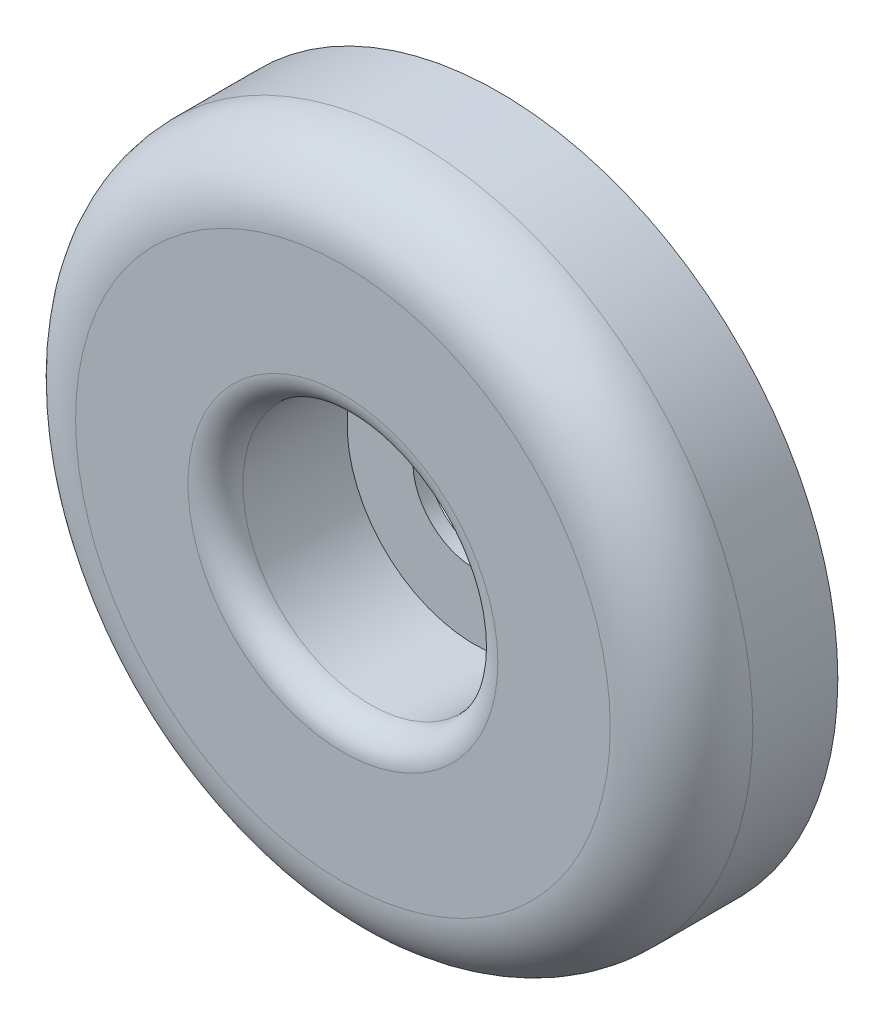
SolidWorks part; units mm, degrees
ref_plane "Plan de face" through (0, 0, 0) normal (0, 0, 1) x (1, 0, 0)
ref_plane "Plan de dessus" through (0, 0, 0) normal (0, 1, 0) x (1, 0, 0)
ref_plane "Plan de droite" through (0, 0, 0) normal (1, 0, 0) x (0, 0, -1)
sketch "Esquisse1" plane through (0, 0, 0) normal (1, 0, 0) x (0, 0, -1)
  line L0 (0, 0) -> (0, 2.25) construction
  line L1 (24.9343, 2.25) -> (-13.052, 2.25) construction
  line L2 (0, 2.25) -> (0.5, 2.25)
  line L3 (0.5, 2.25) -> (0.5, 4.65)
  line L6 (0.9, 12.35) -> (-2.1, 12.35)
  line L7 (0, 2.25) -> (0, 4.65)
  line L11 (-2.1, 12.35) -> (-2.2, 12.35)
  line L13 (-13.052, 0) -> (16.3888, 0) construction
  line L14 (-4.8, 9.75) -> (-4.8, 5.65)
  line L15 (-3.8, 4.65) -> (0, 4.65)
  line L16 (0.9, 12.35) -> (0.9, 4.65)
  line L17 (0.9, 4.65) -> (0.5, 4.65)
  arc A0 (-2.2, 12.35) -> (-4.8, 9.75) centre (-2.2, 9.75) ccw
  arc A1 (-4.8, 5.65) -> (-3.8, 4.65) centre (-3.8, 5.65) ccw
  dimension "D8" = 2.6
  dimension "D9" = 1
  dimension "D1" = 10.1
  dimension "D2" = 2.25
  dimension "D3" = 0.4
  dimension "D4" = 7.7
  dimension "D5" = 3
  dimension "D6" = 0.5
  dimension "D7" = 5.7
  dimension "D10" = 4.1
revolve "Révolution1" add sketch "Esquisse1" angle 360 about L13
